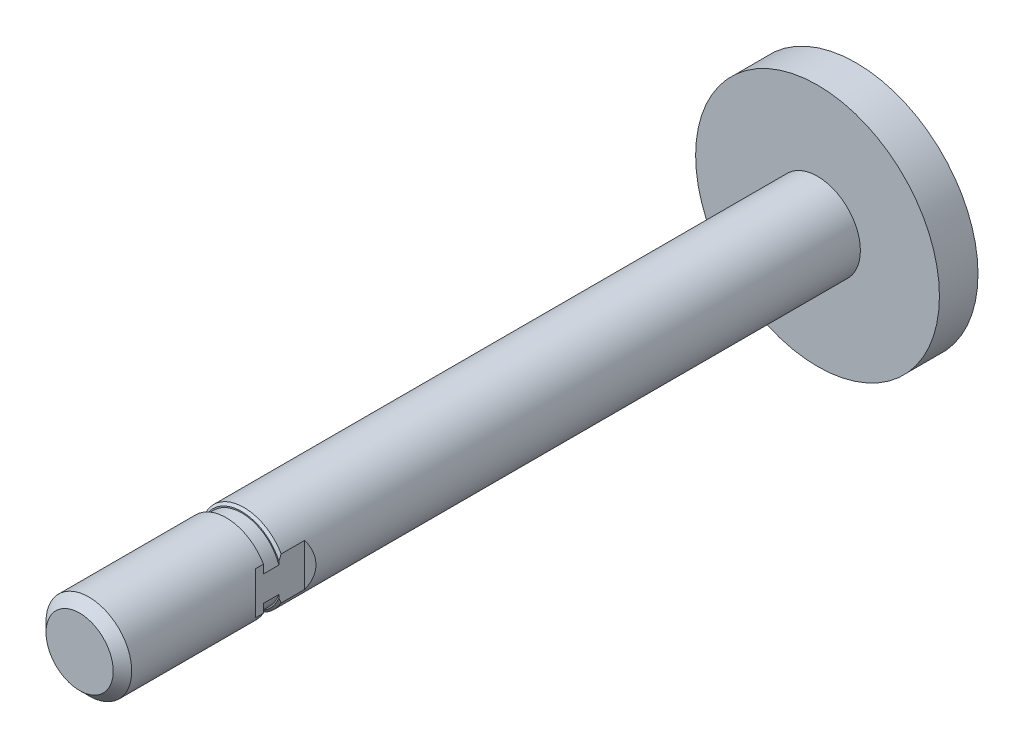
SolidWorks part; units mm, degrees
ref_plane "Front" through (0, 0, 0) normal (0, 0, 1) x (1, 0, 0)
ref_plane "Top" through (0, 0, 0) normal (0, 1, 0) x (1, 0, 0)
ref_plane "Right" through (0, 0, 0) normal (1, 0, 0) x (0, 0, -1)
sketch "Sketch1" plane through (0, 0, 0) normal (0, 0, 1) x (1, 0, 0)
  circle A0 centre (0, 0) radius 5.556
  dimension "D1" = 11.112
extrude "Extrude1" add sketch "Sketch1" along normal up to surface (100.645 mm away)
chamfer "ThreadChamfer" distance 1.2 angle 45 1 edges at (0, 5.556, 100.645)
ref_plane "ThreadEndFront" through (0, 0, 81.645) normal (0, 0, 1) x (1, 0, 0)
ref_plane "ThreadEndBack" through (0, 0, 79.645) normal (0, 0, 1) x (1, 0, 0)
sketch "Sketch3" plane through (0, 0, 81.645) normal (0, 0, 1) x (1, 0, 0)
  circle A0 centre (0, 0) radius 5.1
  dimension "D1" = 10.2
extrude "Cut-Extrude1" cut sketch "Sketch3" against normal up to surface (2 mm away) flip side to cut up to plane "ThreadEndBack"
chamfer "Chamfer2" distance 0.3 angle 45 1 edges at (5.556, 0, 79.645)
sketch "Sketch4" plane through (0, 0, 0) normal (0, 0, 1) x (1, 0, 0)
  circle A0 centre (0, 0) radius 15.8
  dimension "D1" = 31.6
extrude "Piston" add sketch "Sketch4" along normal blind 5
sketch "Sketch5" plane through (0, 0, 0) normal (0, 1, 0) x (1, 0, 0)
  line L0 (0, -100.645) -> (0, 0) construction
  line L1 (5.556, -75.565) -> (4.826, -76.295)
  line L2 (-4.356, -100.645) -> (4.356, -100.645) construction
  line L3 (5.556, 0) -> (-5.556, 0) construction
  line L4 (-5.556, -83.375) -> (-4.826, -82.645)
  line L5 (-5.556, -81.645) -> (-5.556, -99.445) construction
  line L6 (5.556, -83.375) -> (5.556, -75.565)
  line L7 (-4.826, -82.645) -> (-4.826, -76.295)
  line L8 (-5.556, -83.375) -> (-5.556, -75.565)
  line L10 (-4.826, -79.47) -> (0, -79.47) construction
  line L11 (-5.556, -75.565) -> (-4.826, -76.295)
  line L12 (4.826, -82.645) -> (4.826, -76.295)
  line L13 (5.556, -83.375) -> (4.826, -82.645)
  dimension "D2" = 9.652
  dimension "D3" = 18
  dimension "D4" = 6.35
extrude "Cut-Extrude2" cut sketch "Sketch5" against normal up to next and the other way up to next
